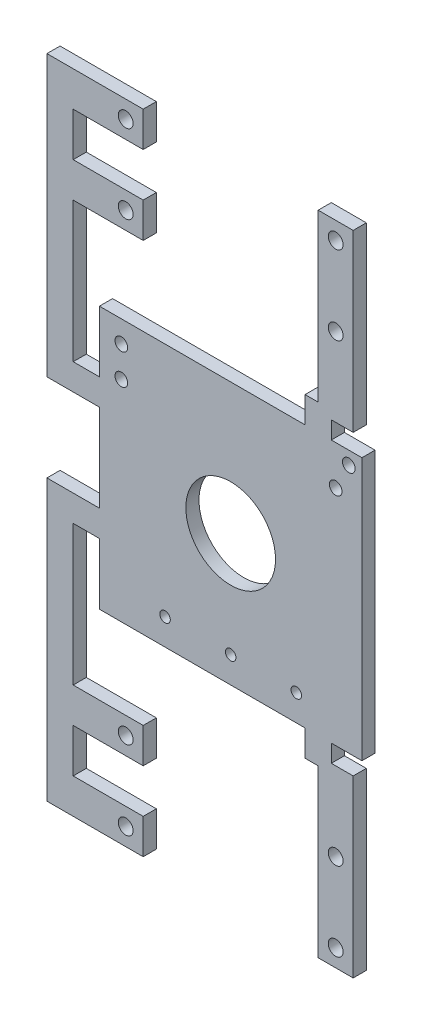
SolidWorks part; units mm, degrees
ref_plane "Front Plane" through (0, 0, 0) normal (0, 0, 1) x (1, 0, 0)
ref_plane "Top Plane" through (0, 0, 0) normal (0, 1, 0) x (1, 0, 0)
ref_plane "Right Plane" through (0, 0, 0) normal (1, 0, 0) x (0, 0, -1)
sketch "Sketch1" plane through (0, 0, 0) normal (0, 0, 1) x (1, 0, 0)
  line L1 (-30, -30) -> (30, -30)
  line L2 (-30, -30) -> (-30, 30)
  line L3 (-30, 30) -> (30, 30)
  line L4 (30, -30) -> (30, 30)
  line L5 (-30, -30) -> (30, 30) construction
  line L6 (-30, 30) -> (30, -30) construction
  point P0 (0, 0)
  dimension "D1" = 60
  dimension "D2" = 60
extrude "Boss-Extrude1" add sketch "Sketch1" along normal blind 3
sketch "Sketch2" plane through (0, 0, 3) normal (0, 0, 1) x (1, 0, 0)
  circle A0 centre (0, 0) radius 10.25
extrude "Cut-Extrude1" cut sketch "Sketch2" against normal through all
sketch "Sketch3" plane through (0, 0, 0) normal (0, 0, -1) x (-1, 0, 0)
  circle A0 centre (-21, 21) radius 1.45
  circle A1 centre (-27, 27) radius 1.45
sketch "Sketch4" plane through (0, 0, 0) normal (0, 0, -1) x (-1, 0, 0)
  circle A0 centre (-24, 21) radius 1.45
  circle A1 centre (-27, 27) radius 1.45
extrude "Stop_Mount_D2p9_Through" cut sketch "Sketch4" against normal blind 3.01
sketch "Sketch5" plane through (0, 0, 0) normal (0, 0, -1) x (-1, 0, 0)
  circle A0 centre (25, 18) radius 1.45
  circle A1 centre (25, 25) radius 1.45
extrude "Servo_X_Mount_D2p9" cut sketch "Sketch5" against normal blind 3.01
sketch "Sketch6" plane through (0, 0, 3) normal (0, 0, 1) x (1, 0, 0)
  circle A0 centre (15, -24) radius 1.2
  circle A1 centre (0, -24) radius 1.2
  circle A2 centre (-15, -24) radius 1.2
extrude "GuideRail2_D2p4" cut sketch "Sketch6" against normal blind 3.01
sketch "Sketch7" plane through (0, 0, 0) normal (0, 0, 1) x (1, 0, 0)
  line L1 (-28, -56) -> (-20, -56)
  line L2 (-28, -56) -> (-28, -24)
  line L3 (-28, -24) -> (-20, -24)
  line L4 (-20, -56) -> (-20, -24)
extrude "Frame_Support_Ear_1" [suppressed] add sketch "Sketch7" along normal blind 3
sketch "Sketch8" plane through (0, 0, 0) normal (0, 0, 1) x (1, 0, 0)
  line L1 (-28, 24) -> (-20, 24)
  line L2 (-28, 24) -> (-28, 56)
  line L3 (-28, 56) -> (-20, 56)
  line L4 (-20, 24) -> (-20, 56)
extrude "Frame_Support_Ear_2" [suppressed] add sketch "Sketch8" along normal blind 3
sketch "Sketch9" plane through (0, 0, 0) normal (0, 0, 1) x (1, 0, 0)
  line L1 (20, -56) -> (28, -56)
  line L2 (20, -56) -> (20, -24)
  line L3 (20, -24) -> (28, -24)
  line L4 (28, -56) -> (28, -24)
extrude "Frame_Support_Ear_3" [suppressed] add sketch "Sketch9" along normal blind 3
sketch "Sketch10" plane through (0, 0, 0) normal (0, 0, 1) x (1, 0, 0)
  line L1 (20, 24) -> (28, 24)
  line L2 (20, 24) -> (20, 56)
  line L3 (20, 56) -> (28, 56)
  line L4 (28, 24) -> (28, 56)
extrude "Frame_Support_Ear_4" [suppressed] add sketch "Sketch10" along normal blind 3
sketch "Sketch11" plane through (0, 0, 3) normal (0, 0, 1) x (1, 0, 0)
  circle A0 centre (-24, -52) radius 1.7
  circle A1 centre (-24, 52) radius 1.7
  circle A2 centre (24, -52) radius 1.7
  circle A3 centre (24, 52) radius 1.7
extrude "Frame_Support_Four_D3p4" [suppressed] cut sketch "Sketch11" against normal blind 3.01
sketch "Sketch12" plane through (0, 0, 0) normal (0, 0, 1) x (1, 0, 0)
  line L1 (-42, 10) -> (-27, 10)
  line L2 (-42, 10) -> (-42, 16)
  line L3 (-42, 16) -> (-27, 16)
  line L4 (-27, 10) -> (-27, 16)
extrude "Routed_Frame_Ear_LeftPlus_Root" add sketch "Sketch12" along normal blind 3
sketch "Sketch13" plane through (0, 0, 0) normal (0, 0, 1) x (1, 0, 0)
  line L1 (-42, 10) -> (-36, 10)
  line L2 (-42, 10) -> (-42, 56)
  line L3 (-42, 56) -> (-36, 56)
  line L4 (-36, 10) -> (-36, 56)
extrude "Routed_Frame_Ear_LeftPlus_Outboard" add sketch "Sketch13" along normal blind 3
sketch "Sketch14" plane through (0, 0, 0) normal (0, 0, 1) x (1, 0, 0)
  line L1 (-42, 48) -> (-20, 48)
  line L2 (-42, 48) -> (-42, 56)
  line L3 (-42, 56) -> (-20, 56)
  line L4 (-20, 48) -> (-20, 56)
extrude "Routed_Frame_Ear_LeftPlus_Pad" add sketch "Sketch14" along normal blind 3
sketch "Sketch15" plane through (0, 0, 0) normal (0, 0, 1) x (1, 0, 0)
  line L1 (-42, -16) -> (-27, -16)
  line L2 (-42, -16) -> (-42, -10)
  line L3 (-42, -10) -> (-27, -10)
  line L4 (-27, -16) -> (-27, -10)
extrude "Routed_Frame_Ear_LeftMinus_Root" add sketch "Sketch15" along normal blind 3
sketch "Sketch16" plane through (0, 0, 0) normal (0, 0, 1) x (1, 0, 0)
  line L1 (-42, -56) -> (-36, -56)
  line L2 (-42, -56) -> (-42, -10)
  line L3 (-42, -10) -> (-36, -10)
  line L4 (-36, -56) -> (-36, -10)
extrude "Routed_Frame_Ear_LeftMinus_Outboard" add sketch "Sketch16" along normal blind 3
sketch "Sketch17" plane through (0, 0, 0) normal (0, 0, 1) x (1, 0, 0)
  line L1 (-42, -56) -> (-20, -56)
  line L2 (-42, -56) -> (-42, -48)
  line L3 (-42, -48) -> (-20, -48)
  line L4 (-20, -56) -> (-20, -48)
extrude "Routed_Frame_Ear_LeftMinus_Pad" add sketch "Sketch17" along normal blind 3
sketch "Sketch18" plane through (0, 0, 0) normal (0, 0, 1) x (1, 0, 0)
  line L1 (17, 28) -> (23, 28)
  line L2 (17, 28) -> (17, 36)
  line L3 (17, 36) -> (23, 36)
  line L4 (23, 28) -> (23, 36)
extrude "Routed_Frame_Ear_RightPlus_Root" add sketch "Sketch18" along normal blind 3
sketch "Sketch19" plane through (0, 0, 0) normal (0, 0, 1) x (1, 0, 0)
  line L1 (20, 34) -> (28, 34)
  line L2 (20, 34) -> (20, 56)
  line L3 (20, 56) -> (28, 56)
  line L4 (28, 34) -> (28, 56)
extrude "Routed_Frame_Ear_RightPlus_Pad" add sketch "Sketch19" along normal blind 3
sketch "Sketch20" plane through (0, 0, 0) normal (0, 0, 1) x (1, 0, 0)
  line L1 (17, -36) -> (23, -36)
  line L2 (17, -36) -> (17, -28)
  line L3 (17, -28) -> (23, -28)
  line L4 (23, -36) -> (23, -28)
extrude "Routed_Frame_Ear_RightMinus_Root" add sketch "Sketch20" along normal blind 3
sketch "Sketch21" plane through (0, 0, 0) normal (0, 0, 1) x (1, 0, 0)
  line L1 (20, -56) -> (28, -56)
  line L2 (20, -56) -> (20, -34)
  line L3 (20, -34) -> (28, -34)
  line L4 (28, -56) -> (28, -34)
extrude "Routed_Frame_Ear_RightMinus_Pad" add sketch "Sketch21" along normal blind 3
sketch "Sketch22" plane through (0, 0, 3) normal (0, 0, 1) x (1, 0, 0)
  circle A0 centre (-24, -52) radius 1.7
  circle A1 centre (-24, 52) radius 1.7
  circle A2 centre (24, -52) radius 1.7
  circle A3 centre (24, 52) radius 1.7
extrude "Routed_Frame_Ears_D3p4" cut sketch "Sketch22" against normal blind 3.01
sketch "Sketch23" plane through (0, 0, 0) normal (0, 0, 1) x (1, 0, 0)
  line L1 (-42, 54) -> (-36, 54)
  line L2 (-42, 54) -> (-42, 74)
  line L3 (-42, 74) -> (-36, 74)
  line L4 (-36, 54) -> (-36, 74)
extrude "Four_Link_Support_Plus_LeftRail" add sketch "Sketch23" along normal blind 3
sketch "Sketch24" plane through (0, 0, 0) normal (0, 0, 1) x (1, 0, 0)
  line L1 (-42, 66) -> (-20, 66)
  line L2 (-42, 66) -> (-42, 74)
  line L3 (-42, 74) -> (-20, 74)
  line L4 (-20, 66) -> (-20, 74)
extrude "Four_Link_Support_Plus_LeftPad" add sketch "Sketch24" along normal blind 3
sketch "Sketch25" plane through (0, 0, 0) normal (0, 0, 1) x (1, 0, 0)
  line L1 (20, 54) -> (28, 54)
  line L2 (20, 54) -> (20, 74)
  line L3 (20, 74) -> (28, 74)
  line L4 (28, 54) -> (28, 74)
extrude "Four_Link_Support_Plus_RightRail" add sketch "Sketch25" along normal blind 3
sketch "Sketch26" plane through (0, 0, 0) normal (0, 0, 1) x (1, 0, 0)
  line L1 (-42, -74) -> (-36, -74)
  line L2 (-42, -74) -> (-42, -54)
  line L3 (-42, -54) -> (-36, -54)
  line L4 (-36, -74) -> (-36, -54)
extrude "Four_Link_Support_Minus_LeftRail" add sketch "Sketch26" along normal blind 3
sketch "Sketch27" plane through (0, 0, 0) normal (0, 0, 1) x (1, 0, 0)
  line L1 (-42, -74) -> (-20, -74)
  line L2 (-42, -74) -> (-42, -66)
  line L3 (-42, -66) -> (-20, -66)
  line L4 (-20, -74) -> (-20, -66)
extrude "Four_Link_Support_Minus_LeftPad" add sketch "Sketch27" along normal blind 3
sketch "Sketch28" plane through (0, 0, 0) normal (0, 0, 1) x (1, 0, 0)
  line L1 (20, -74) -> (28, -74)
  line L2 (20, -74) -> (20, -54)
  line L3 (20, -54) -> (28, -54)
  line L4 (28, -74) -> (28, -54)
extrude "Four_Link_Support_Minus_RightRail" add sketch "Sketch28" along normal blind 3
sketch "Sketch29" plane through (0, 0, 3) normal (0, 0, 1) x (1, 0, 0)
  circle A0 centre (-24, -70) radius 1.7
  circle A1 centre (-24, 70) radius 1.7
  circle A2 centre (24, -70) radius 1.7
  circle A3 centre (24, 70) radius 1.7
extrude "Four_Link_Support_Holes_Y70" cut sketch "Sketch29" against normal blind 3.01
